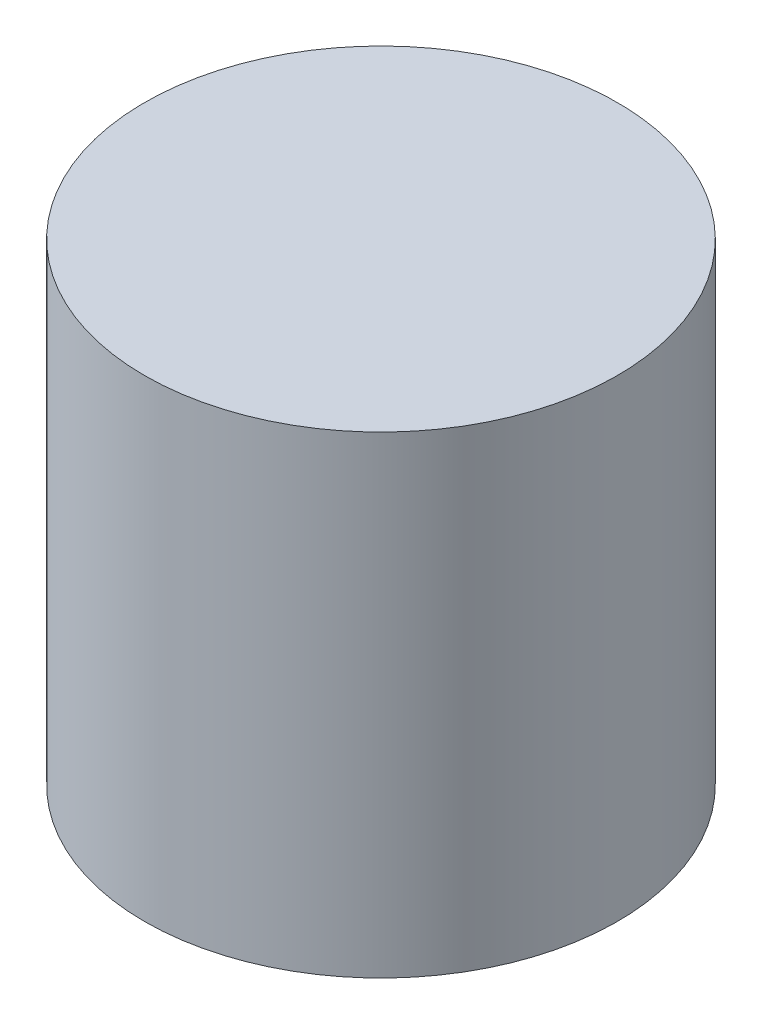
SolidWorks part; units mm, degrees
ref_plane "Plan de face" through (0, 0, 0) normal (0, 0, 1) x (1, 0, 0)
ref_plane "Plan de dessus" through (0, 0, 0) normal (0, 1, 0) x (1, 0, 0)
ref_plane "Plan de droite" through (0, 0, 0) normal (1, 0, 0) x (0, 0, -1)
sketch "Esquisse14" plane through (0, 0, 0) normal (0, 1, 0) x (1, 0, 0)
  circle A0 centre (0, 0) radius 50
extrude "Boss.-Extru.2" add sketch "Esquisse14" along normal blind 100
ref_plane "Plan4" through (0, 50, 0) normal (0, 1, 0) x (1, 0, 0)
ref_plane "Plan5" through (0, 0, 0) normal (0, 1, 0) x (1, 0, 0)
sketch "Esquisse17" plane through (0, 100, 0) normal (0, 1, 0) x (1, 0, 0)
  circle A0 centre (0, 0) radius 15.507
sketch "Esquisse18" plane through (0, 50, 0) normal (0, 1, 0) x (1, 0, 0)
  line L1 (38.4898, 33.896) -> (-38.4898, 33.896)
  line L2 (38.4898, 33.896) -> (38.4898, -33.896)
  line L3 (38.4898, -33.896) -> (-38.4898, -33.896)
  line L4 (-38.4898, 33.896) -> (-38.4898, -33.896)
  line L5 (38.4898, 33.896) -> (-38.4898, -33.896) construction
  line L6 (38.4898, -33.896) -> (-38.4898, 33.896) construction
  point P0 (0, 0)
sketch "Esquisse19" plane through (0, 0, 0) normal (0, 1, 0) x (1, 0, 0)
  line L0 (10.671, 26.2818) -> (-21.698, 18.2702)
  line L1 (-24.0811, -14.9902) -> (6.8151, -27.5347)
  line L2 (6.8151, -27.5347) -> (28.293, -2.0272)
  line L3 (28.293, -2.0272) -> (10.671, 26.2818)
  line L4 (-21.698, 18.2702) -> (-24.0811, -14.9902)
  circle A0 centre (0, 0) radius 22.9482 construction
